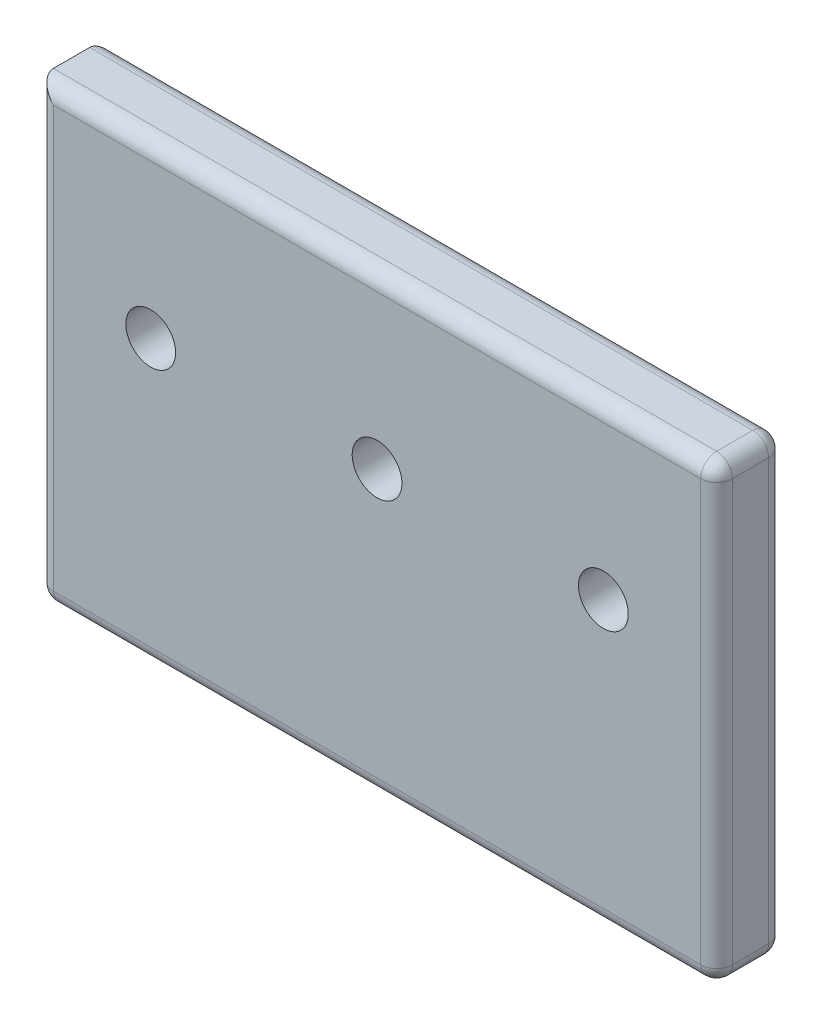
SolidWorks part; units mm, degrees
ref_plane "前视基准面" through (0, 0, 0) normal (0, 0, 1) x (1, 0, 0)
ref_plane "上视基准面" through (0, 0, 0) normal (0, 1, 0) x (1, 0, 0)
ref_plane "右视基准面" through (0, 0, 0) normal (1, 0, 0) x (0, 0, -1)
other "Configuration Table"
sketch "草图1" plane through (0, 0, 0) normal (0, 0, 1) x (1, 0, 0)
  line L0 (55, 0) -> (-55, 0) construction
  line L1 (-8, 3) -> (8, 3)
  line L2 (-8, 3) -> (-8, 0)
  line L3 (-8, 0) -> (8, 0)
  line L4 (8, 3) -> (8, 0)
  line L5 (0, -55) -> (0, 55) construction
  dimension "D1" = 16
  dimension "D2" = 8
  dimension "D3" = 3
extrude "凸台-拉伸1" add sketch "草图1" against normal blind 10
sketch "草图2" plane through (0, 0, 0) normal (0, 0, 1) x (1, 0, 0)
  line L8 (-8, 0) -> (22, 0)
  line L9 (-8, 0) -> (-8, 20)
  line L10 (-8, 20) -> (22, 20)
  line L11 (22, 0) -> (22, 20)
  dimension "D1" = 30
  dimension "D2" = 20
extrude "凸台-拉伸2" add sketch "草图2" along normal blind 3
hole_wizard "Ø2.2 (2.2) 直径孔1" positions "草图3" profile "草图4" hole size "Ø2.2" standard "ANSI Metric" end condition up to next
sketch "草图3" plane through (0, 3, 0) normal (0, 1, 0) x (1, 0, 0)
  line L0 (8, 0) -> (-8, 0) construction
  line L2 (-8, 10) -> (-8, 0) construction
  point P0 (-5, 5)
  point P2 (5, 5)
  dimension "D1" = 5
  dimension "D2" = 10
  dimension "D3" = 3
  dimension "D4" = 5
sketch "草图4" plane through (-5, 3, -5) normal (1, 0, 0) x (0, 0, 1)
  line L0 (0, 0) -> (0, 3)
  line L1 (0, 3) -> (1.1, 3)
  line L2 (1.1, 3) -> (1.1, 0)
  line L5 (1.1, 0) -> (0, 0)
  line L11 (0, -6.35) -> (0, 107.95) construction
  dimension "通孔孔直径" = 2.2
  dimension "通孔孔深度" = 3
fillet "圆角1" radius 0.7 20 edges at (7, 0, 3) (22, 0, 1.5) (15, 0, 0) (-8, 11.5, 0) (-8, 0, -3.5) (22, 10, 0) (22, 10, 3) (8, 0, -5) (-8, 3, -5) (-8, 1.5, -10) (0, 0, -10) (8, 1.5, -10) (0, 3, -10) (0, 3, 0) (8, 3, -5) (8, 1.5, 0) (7, 20, 0) (7, 20, 3) (22, 20, 1.5) (-8, 10, 3)
hole_wizard "Ø2.2 (2.2) 直径孔2" positions "草图5" profile "草图6" hole size "Ø2.2" standard "ANSI Metric" end condition up to next
sketch "草图5" plane through (0, 0, 0) normal (0, 0, -1) x (-1, 0, 0)
  line L0 (-8.7, 0) -> (-21.3, 0) construction
  line L1 (8, 20) -> (8, 3.7) construction
  point P0 (-17, 12.52)
  point P2 (-7, 12.52)
  point P4 (3, 12.52)
  dimension "D1" = 12.52
  dimension "D2" = 12.52
  dimension "D3" = 12.52
  dimension "D4" = 5
  dimension "D5" = 10
  dimension "D6" = 10
sketch "草图6" plane through (17, 12.52, 0) normal (1, 0, 0) x (0, 1, 0)
  line L0 (0, 0) -> (0, 3)
  line L1 (0, 3) -> (1.1, 3)
  line L2 (1.1, 3) -> (1.1, 0)
  line L5 (1.1, 0) -> (0, 0)
  line L11 (0, -6.35) -> (0, 107.95) construction
  dimension "通孔孔直径" = 2.2
  dimension "通孔孔深度" = 3
